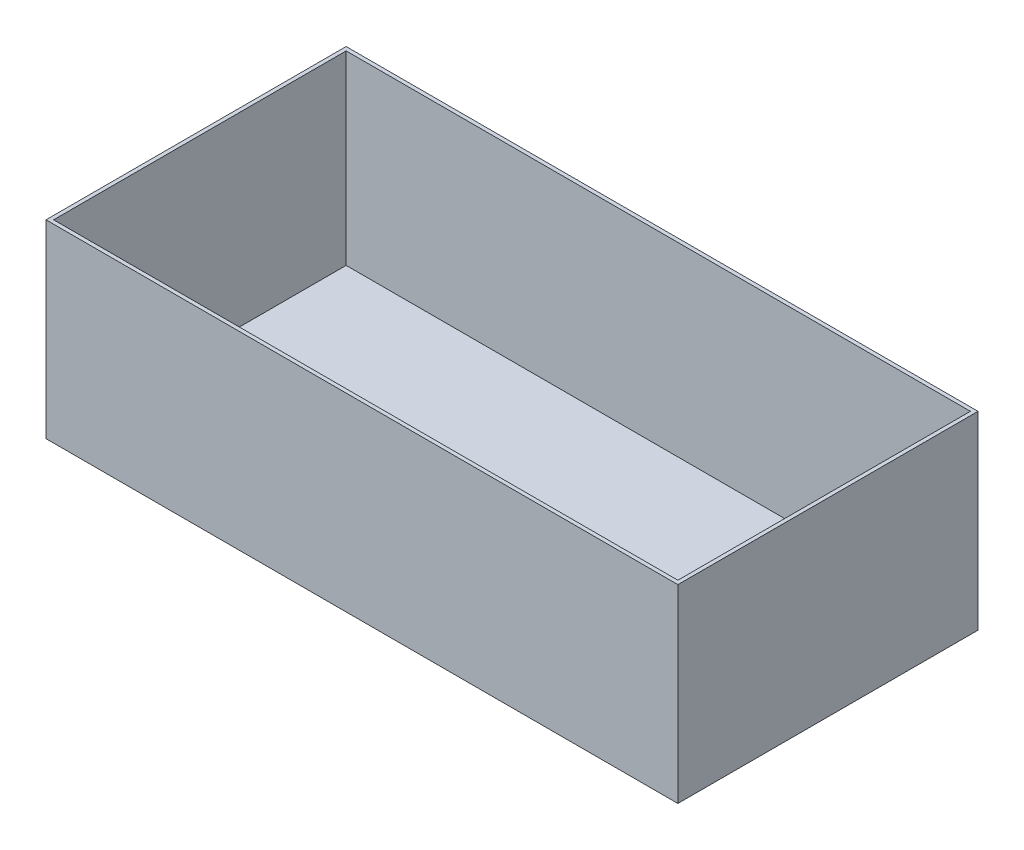
SolidWorks part; units mm, degrees
ref_plane "Front Plane" through (0, 0, 0) normal (0, 0, 1) x (1, 0, 0)
ref_plane "Top Plane" through (0, 0, 0) normal (0, 1, 0) x (1, 0, 0)
ref_plane "Right Plane" through (0, 0, 0) normal (1, 0, 0) x (0, 0, -1)
sketch "Sketch1" plane through (0, 0, 0) normal (0, 1, 0) x (1, 0, 0)
  line L1 (0, 0) -> (200, 0)
  line L2 (0, 0) -> (0, 95)
  line L3 (0, 95) -> (200, 95)
  line L4 (200, 0) -> (200, 95)
  dimension "D1" = 200
  dimension "D2" = 95
extrude "Boss-Extrude1" add sketch "Sketch1" along normal blind 60
sketch "Sketch2" plane through (0, 60, 0) normal (0, 1, 0) x (1, 0, 0)
  line L0 (200, 95) -> (0, 95) construction
  line L1 (1.2, 93.8) -> (198.8, 93.8)
  line L2 (1.2, 93.8) -> (1.2, 1.2)
  line L3 (1.2, 1.2) -> (198.8, 1.2)
  line L4 (198.8, 93.8) -> (198.8, 1.2)
  line L5 (0, 95) -> (0, 0) construction
  line L6 (0, 0) -> (200, 0) construction
  line L7 (200, 0) -> (200, 95) construction
  dimension "D1" = 1.2
  dimension "D2" = 1.2
  dimension "D3" = 1.2
  dimension "D4" = 1.2
extrude "Cut-Extrude1" cut sketch "Sketch2" against normal blind 58.8
